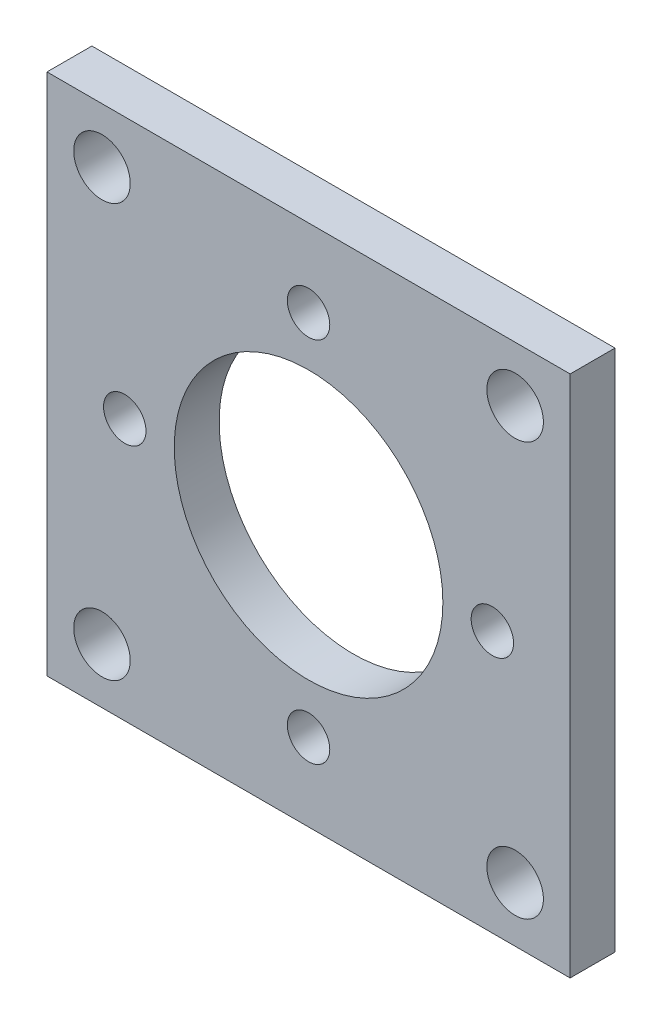
SolidWorks part; units mm, degrees
ref_plane "Front Plane" through (0, 0, 0) normal (0, 0, 1) x (1, 0, 0)
ref_plane "Top Plane" through (0, 0, 0) normal (0, 1, 0) x (1, 0, 0)
ref_plane "Right Plane" through (0, 0, 0) normal (1, 0, 0) x (0, 0, -1)
sketch "Sketch1" plane through (0, 0, 0) normal (0, 0, 1) x (1, 0, 0)
  line L1 (-18.5, 18.5) -> (18.5, 18.5)
  line L2 (-18.5, 18.5) -> (-18.5, -18.5)
  line L3 (-18.5, -18.5) -> (18.5, -18.5)
  line L4 (18.5, 18.5) -> (18.5, -18.5)
  line L5 (-18.5, 18.5) -> (18.5, -18.5) construction
  line L6 (-18.5, -18.5) -> (18.5, 18.5) construction
  point P0 (0, 0)
  dimension "D1" = 37
  dimension "D2" = 37
extrude "Boss-Extrude1" add sketch "Sketch1" along normal blind 3.175
sketch "Sketch2" plane through (0, 0, 3.175) normal (0, 0, 1) x (1, 0, 0)
  circle A0 centre (0, 0) radius 9.5
  dimension "D1" = 19
extrude "Cut-Extrude1" cut sketch "Sketch2" against normal through all
sketch "Sketch3" plane through (0, 0, 3.175) normal (0, 0, 1) x (1, 0, 0)
  line L0 (-18.5, 0) -> (18.5, 0) construction
  line L1 (-18.5, 18.5) -> (-18.5, -18.5) construction
  line L2 (18.5, -18.5) -> (18.5, 18.5) construction
  line L3 (0, 18.5) -> (0, -18.5) construction
  line L4 (18.5, 18.5) -> (-18.5, 18.5) construction
  line L5 (-18.5, -18.5) -> (18.5, -18.5) construction
  circle A0 centre (-13, 0) radius 1.5
  circle A1 centre (0, 13) radius 1.5
  circle A2 centre (13, 0) radius 1.5
  circle A3 centre (0, -13) radius 1.5
  point P12 (-13, 0)
  point P13 (13, 0)
  point P14 (0, 13)
  point P15 (0, -13)
  dimension "D5" = 3
  dimension "D6" = 3
  dimension "D7" = 3
  dimension "D8" = 3
  dimension "D1" = 13
  dimension "D2" = 13
  dimension "D3" = 13
  dimension "D4" = 13
extrude "Cut-Extrude2" cut sketch "Sketch3" against normal through all
sketch "Sketch4" plane through (0, 0, 3.175) normal (0, 0, 1) x (1, 0, 0)
  line L0 (-18.5, 18.5) -> (18.5, -18.5) construction
  line L1 (18.5, 18.5) -> (-18.5, -18.5) construction
  circle A0 centre (-14.6109, 14.6109) radius 2
  circle A1 centre (14.6109, 14.6109) radius 2
  circle A2 centre (14.6109, -14.6109) radius 2
  circle A3 centre (-14.6109, -14.6109) radius 2
  point P8 (-14.6109, 14.6109)
  point P9 (14.6109, 14.6109)
  point P10 (14.6109, -14.6109)
  point P11 (-14.6109, -14.6109)
  dimension "D5" = 4
  dimension "D6" = 4
  dimension "D7" = 4
  dimension "D8" = 4
  dimension "D1" = 5.5
  dimension "D2" = 5.5
  dimension "D3" = 5.5
  dimension "D4" = 5.5
extrude "Cut-Extrude3" cut sketch "Sketch4" against normal through all
